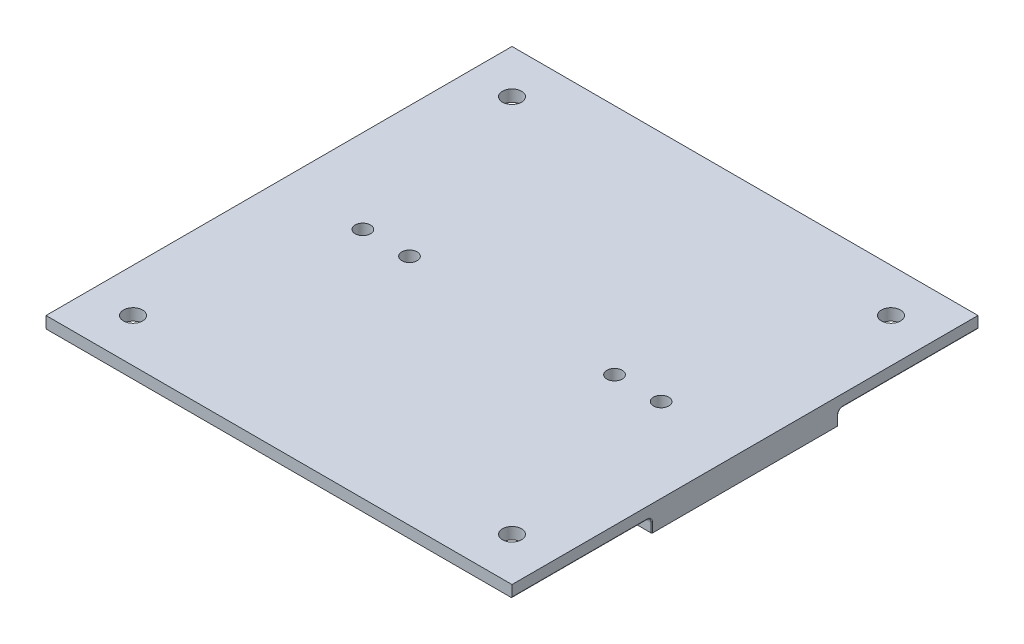
SolidWorks part; units mm, degrees
material "6061-T6 (SS)"
ref_plane "Front Plane" through (0, 0, 0) normal (0, 0, 1) x (1, 0, 0)
ref_plane "Top Plane" through (0, 0, 0) normal (0, 1, 0) x (1, 0, 0)
ref_plane "Right Plane" through (0, 0, 0) normal (1, 0, 0) x (0, 0, -1)
sketch "Sketch1" plane through (0, 0, 0) normal (0, 1, 0) x (1, 0, 0)
  line L1 (-50, 50) -> (50, 50)
  line L2 (-50, 50) -> (-50, -50)
  line L3 (-50, -50) -> (50, -50)
  line L4 (50, 50) -> (50, -50)
  line L5 (-50, 50) -> (50, -50) construction
  line L6 (-50, -50) -> (50, 50) construction
  line L7 (-40.66, 40.66) -> (40.66, 40.66) construction
  line L8 (-40.66, 40.66) -> (-40.66, -40.66) construction
  line L9 (-40.66, -40.66) -> (40.66, -40.66) construction
  line L10 (40.66, 40.66) -> (40.66, -40.66) construction
  line L11 (-40.66, 40.66) -> (40.66, -40.66) construction
  line L12 (-40.66, -40.66) -> (40.66, 40.66) construction
  circle A0 centre (-40.66, 40.66) radius 2.05
  circle A1 centre (40.66, 40.66) radius 2.05
  circle A2 centre (40.66, -40.66) radius 2.05
  circle A3 centre (-40.66, -40.66) radius 2.05
  point P0 (0, 0)
  point P6 (0, 0)
  dimension "D5" = 4.1
  dimension "D1" = 100
  dimension "D2" = 100
  dimension "D3" = 81.32
  dimension "D4" = 81.32
extrude "Boss-Extrude1" add sketch "Sketch1" along normal blind 2.5
sketch "Sketch3" plane through (0, 0, 0) normal (0, -1, 0) x (1, 0, 0)
  line L0 (-50, 0) -> (50, 0) construction
  line L1 (-50, 20) -> (50, 20)
  line L2 (-50, 20) -> (-50, -20)
  line L3 (-50, -20) -> (50, -20)
  line L4 (50, 20) -> (50, -20)
  line L5 (-50, 20) -> (50, -20) construction
  line L6 (-50, -20) -> (50, 20) construction
  line L7 (-50, -50) -> (-50, 50) construction
  line L8 (50, 50) -> (50, -50) construction
  line L9 (-50, -50) -> (-50, 50) construction
  point P0 (0, 0)
  dimension "D1" = 40
extrude "Boss-Extrude2" add sketch "Sketch3" along normal blind 3
fillet "Fillet2" radius 1 2 edges at (0, 0, -20) (0, 0, 20)
fillet "Fillet4" radius 0.2 12 edges at (-50, -2, -20) (-50, -2, 20) (50, -2, -20) (50, -2, 20) (-50, 0, -35.5) (-50, -0.2929, -20.2929) (-50, 0, 35.5) (-50, -0.2929, 20.2929) (50, 0, -35.5) (50, -0.2929, -20.2929) (50, 0, 35.5) (50, -0.2929, 20.2929)
sketch "Sketch4" plane through (0, -3, 0) normal (0, -1, 0) x (1, 0, 0)
  line L1 (-37.5, 6.35) -> (37.5, 6.35)
  line L2 (-37.5, 6.35) -> (-37.5, -6.35)
  line L3 (-37.5, -6.35) -> (37.5, -6.35)
  line L4 (37.5, 6.35) -> (37.5, -6.35)
  line L5 (-37.5, 6.35) -> (37.5, -6.35) construction
  line L6 (-37.5, -6.35) -> (37.5, 6.35) construction
  line L11 (0, 6.35) -> (0, -6.35) construction
  line L15 (-37.5, 0) -> (37.5, 0) construction
  circle A0 centre (-32, 0) radius 1.65
  circle A1 centre (-22, 0) radius 1.65
  circle A2 centre (22, 0) radius 1.65
  circle A3 centre (32, 0) radius 1.65
  circle A4 centre (-32, 0) radius 1.625
  circle A5 centre (-22, 0) radius 1.625
  circle A6 centre (22, 0) radius 1.625
  circle A7 centre (32, 0) radius 1.625
  point P0 (0, 0)
  point P6 (0, 0)
  dimension "D3" = 5.5
  dimension "D7" = 3.3
  dimension "D8" = 3.25
  dimension "D1" = 75
  dimension "D2" = 12.7
  dimension "D4" = 5.5
  dimension "D5" = 15.5
  dimension "D6" = 15.5
extrude "Cut-Extrude1" cut sketch "Sketch4" against normal through all contours A3 | A2 | A1 | A0
